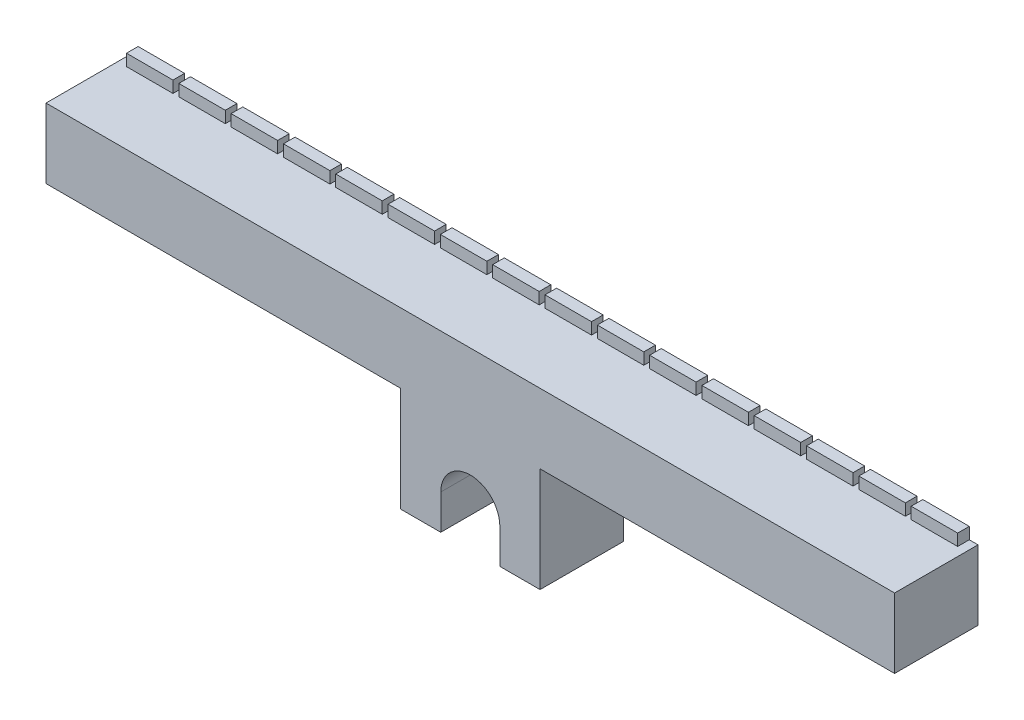
SolidWorks part; units mm, degrees
material "6061-T6 (SS)"
ref_plane "Front" through (0, 0, 0) normal (0, 0, 1) x (1, 0, 0)
ref_plane "Top" through (0, 0, 0) normal (0, 1, 0) x (1, 0, 0)
ref_plane "Right" through (0, 0, 0) normal (1, 0, 0) x (0, 0, -1)
sketch "Sketch1" plane through (0, 0, 0) normal (0, 1, 0) x (1, 0, 0)
  line L1 (-36.5, -6.675) -> (36.5, -6.675)
  line L2 (-36.5, -6.675) -> (-36.5, 0.5)
  line L3 (-36.5, 0.5) -> (36.5, 0.5)
  line L4 (36.5, -6.675) -> (36.5, 0.5)
  point P7 (0, -6.675)
  dimension "D1" = 7.175
  dimension "D2" = 73
  dimension "D3" = 0.5
extrude "Boss-Extrude1" add sketch "Sketch1" along normal blind 6
sketch "Sketch15" plane through (0, 6, 0) normal (0, 1, 0) x (1, 0, 0)
  line L0 (0, 13.2788) -> (0, 21.5564) construction
  line L2 (0.25, 0.5) -> (4.25, 0.5)
  line L3 (0.25, 0.5) -> (0.25, -0.5)
  line L4 (0.25, -0.5) -> (4.25, -0.5)
  line L5 (4.25, 0.5) -> (4.25, -0.5)
  line L7 (4.75, 0.5) -> (8.75, 0.5)
  line L8 (4.75, 0.5) -> (4.75, -0.5)
  line L9 (4.75, -0.5) -> (8.75, -0.5)
  line L10 (8.75, 0.5) -> (8.75, -0.5)
  line L11 (9.25, 0.5) -> (13.25, 0.5)
  line L12 (9.25, 0.5) -> (9.25, -0.5)
  line L13 (9.25, -0.5) -> (13.25, -0.5)
  line L14 (13.25, 0.5) -> (13.25, -0.5)
  line L15 (13.75, 0.5) -> (17.75, 0.5)
  line L16 (13.75, 0.5) -> (13.75, -0.5)
  line L17 (13.75, -0.5) -> (17.75, -0.5)
  line L18 (17.75, 0.5) -> (17.75, -0.5)
  line L19 (18.25, 0.5) -> (22.25, 0.5)
  line L20 (18.25, 0.5) -> (18.25, -0.5)
  line L21 (18.25, -0.5) -> (22.25, -0.5)
  line L22 (22.25, 0.5) -> (22.25, -0.5)
  line L23 (22.75, 0.5) -> (26.75, 0.5)
  line L24 (22.75, 0.5) -> (22.75, -0.5)
  line L25 (22.75, -0.5) -> (26.75, -0.5)
  line L26 (26.75, 0.5) -> (26.75, -0.5)
  line L27 (27.25, 0.5) -> (31.25, 0.5)
  line L28 (27.25, 0.5) -> (27.25, -0.5)
  line L29 (27.25, -0.5) -> (31.25, -0.5)
  line L30 (31.25, 0.5) -> (31.25, -0.5)
  line L31 (31.75, 0.5) -> (35.75, 0.5)
  line L32 (31.75, 0.5) -> (31.75, -0.5)
  line L33 (31.75, -0.5) -> (35.75, -0.5)
  line L34 (35.75, 0.5) -> (35.75, -0.5)
  line L35 (-35.75, 0.5) -> (-35.75, -0.5)
  line L36 (-31.75, -0.5) -> (-35.75, -0.5)
  line L37 (-31.75, 0.5) -> (-31.75, -0.5)
  line L38 (-31.75, 0.5) -> (-35.75, 0.5)
  line L39 (-31.25, 0.5) -> (-31.25, -0.5)
  line L40 (-27.25, -0.5) -> (-31.25, -0.5)
  line L41 (-27.25, 0.5) -> (-27.25, -0.5)
  line L42 (-27.25, 0.5) -> (-31.25, 0.5)
  line L43 (-26.75, 0.5) -> (-26.75, -0.5)
  line L44 (-22.75, -0.5) -> (-26.75, -0.5)
  line L45 (-22.75, 0.5) -> (-22.75, -0.5)
  line L46 (-22.75, 0.5) -> (-26.75, 0.5)
  line L47 (-22.25, 0.5) -> (-22.25, -0.5)
  line L48 (-18.25, -0.5) -> (-22.25, -0.5)
  line L49 (-18.25, 0.5) -> (-18.25, -0.5)
  line L50 (-18.25, 0.5) -> (-22.25, 0.5)
  line L51 (-17.75, 0.5) -> (-17.75, -0.5)
  line L52 (-13.75, -0.5) -> (-17.75, -0.5)
  line L53 (-13.75, 0.5) -> (-13.75, -0.5)
  line L54 (-13.75, 0.5) -> (-17.75, 0.5)
  line L55 (-13.25, 0.5) -> (-13.25, -0.5)
  line L56 (-9.25, -0.5) -> (-13.25, -0.5)
  line L57 (-9.25, 0.5) -> (-9.25, -0.5)
  line L58 (-9.25, 0.5) -> (-13.25, 0.5)
  line L59 (-8.75, 0.5) -> (-8.75, -0.5)
  line L60 (-4.75, -0.5) -> (-8.75, -0.5)
  line L61 (-4.75, 0.5) -> (-4.75, -0.5)
  line L62 (-4.75, 0.5) -> (-8.75, 0.5)
  line L63 (-4.25, 0.5) -> (-4.25, -0.5)
  line L64 (-0.25, -0.5) -> (-4.25, -0.5)
  line L65 (-0.25, 0.5) -> (-0.25, -0.5)
  line L66 (-0.25, 0.5) -> (-4.25, 0.5)
  point P7 (0.25, 0)
  point P11 (2.25, 0.5)
  point P12 (-33.75, 0.5)
  point P13 (-29.25, 0.5)
  point P18 (6.75, 0.5)
  point P23 (11.25, 0.5)
  point P28 (15.75, 0.5)
  point P33 (20.25, 0.5)
  point P38 (24.75, 0.5)
  point P43 (29.25, 0.5)
  point P48 (33.75, 0.5)
  point P49 (-24.75, 0.5)
  point P50 (-20.25, 0.5)
  point P51 (-15.75, 0.5)
  point P52 (-11.25, 0.5)
  point P53 (-6.75, 0.5)
  point P54 (-2.25, 0.5)
  dimension "D1" = 4
  dimension "D2" = 4.5
  dimension "D4" = 4.5
  dimension "D5" = 1
  dimension "D3" = 8
extrude "Boss-Extrude6" add sketch "Sketch15" along normal blind 1
sketch "Sketch16" plane through (0, 0, 0) normal (0, 0, 1) x (1, 0, 0)
  line L0 (-36.5, 0) -> (36.5, 0) construction
  line L1 (21, 0) -> (29, 0) construction
  line L2 (21, 0) -> (21, -3) construction
  line L3 (21, -3) -> (29, -3) construction
  line L4 (29, 0) -> (29, -3) construction
  line L5 (0, -1.9017) -> (0, -7.24) construction
  line L6 (-29, 0) -> (-29, -3) construction
  line L7 (-21, -3) -> (-29, -3) construction
  line L8 (-21, 0) -> (-21, -3) construction
  line L9 (-21, 0) -> (-29, 0) construction
  line L10 (-2.54, -6) -> (-2.54, -9)
  line L11 (-6, 0) -> (6, 0)
  line L12 (-6, 0) -> (-6, -9)
  line L13 (-6, -9) -> (-2.54, -9)
  line L14 (6, 0) -> (6, -9)
  line L17 (2.54, -6) -> (2.54, -9)
  line L18 (2.54, -9) -> (6, -9)
  arc A0 (2.54, -6) -> (-2.54, -6) centre (0, -6) ccw
  point P7 (25, 0)
  point P18 (0, 0)
  dimension "D6" = 5.08
  dimension "D1" = 8
  dimension "D2" = 50
  dimension "D3" = 3
  dimension "D4" = 12
  dimension "D5" = 9
  dimension "D7" = 6
extrude "Boss-Extrude7" add sketch "Sketch16" along normal up to surface and the other way up to surface
sketch "Sketch17" plane through (0, -9, 0) normal (0, -1, 0) x (1, 0, 0)
  line L0 (6, 6.675) -> (6, -0.5) construction
  line L1 (-6, 1.5) -> (6, 1.5)
  line L2 (-6, 1.5) -> (-6, 4.675)
  line L3 (-6, 4.675) -> (6, 4.675)
  line L4 (6, 1.5) -> (6, 4.675)
  line L5 (-6, 1.5) -> (6, 4.675) construction
  line L6 (-6, 4.675) -> (6, 1.5) construction
  line L7 (-6, 6.675) -> (-6, -0.5) construction
  point P0 (0, 3.0875)
  point P9 (-6, 3.0875)
  dimension "D1" = 3.175
extrude "Cut-Extrude1" [suppressed] cut sketch "Sketch17" against normal up to surface (9 mm away)
sketch "Sketch18" plane through (0, 0, 0) normal (1, 0, 0) x (0, 0, -1)
  line L0 (-2, -9) -> (-2, 0)
  line L1 (-6.675, -9) -> (0.5, -9) construction
  line L2 (-6.675, 0) -> (0.5, 0) construction
  line L3 (-2, 0) -> (-4.5, 0)
  line L4 (-4.5, 0) -> (-4.5, 6)
  line L5 (-6.675, 6) -> (0.5, 6) construction
  line L6 (-4.5, 6) -> (-6.675, 6)
  line L7 (-6.675, 6) -> (-6.675, -9)
  line L8 (-6.675, -9) -> (-2, -9)
  line L9 (0.5, 0) -> (0.5, -9) construction
  line L10 (0.5, 6) -> (0.5, 0) construction
  dimension "D1" = 2.5
  dimension "D2" = 5
extrude "Cut-Extrude2" [suppressed] cut sketch "Sketch18" against normal through all both and the other way through all
